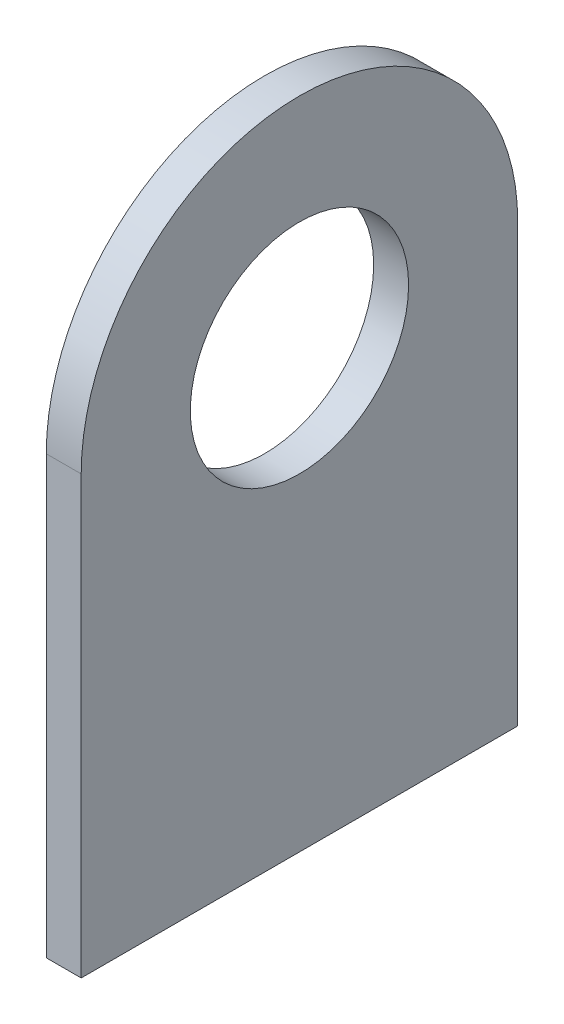
SolidWorks part; units mm, degrees
material "Q235"
ref_plane "前视基准面" through (0, 0, 0) normal (0, 0, 1) x (1, 0, 0)
ref_plane "上视基准面" through (0, 0, 0) normal (0, 1, 0) x (1, 0, 0)
ref_plane "右视基准面" through (0, 0, 0) normal (1, 0, 0) x (0, 0, -1)
sketch "草图1" plane through (0, 0, 0) normal (1, 0, 0) x (0, 0, -1)
  line L0 (0, 0) -> (0, 157.3532) construction
  line L1 (-50, 0) -> (50, 0)
  line L2 (50, 0) -> (50, 100)
  line L3 (-50, 0) -> (-50, 100)
  arc A0 (50, 100) -> (-50, 100) centre (0, 100) ccw
  circle A1 centre (0, 100) radius 25
  point P8 (0, 150)
  dimension "D1" = 150
  dimension "D3" = 50
  dimension "D2" = 100
extrude "凸台-拉伸1" add sketch "草图1" along normal mid plane 8
